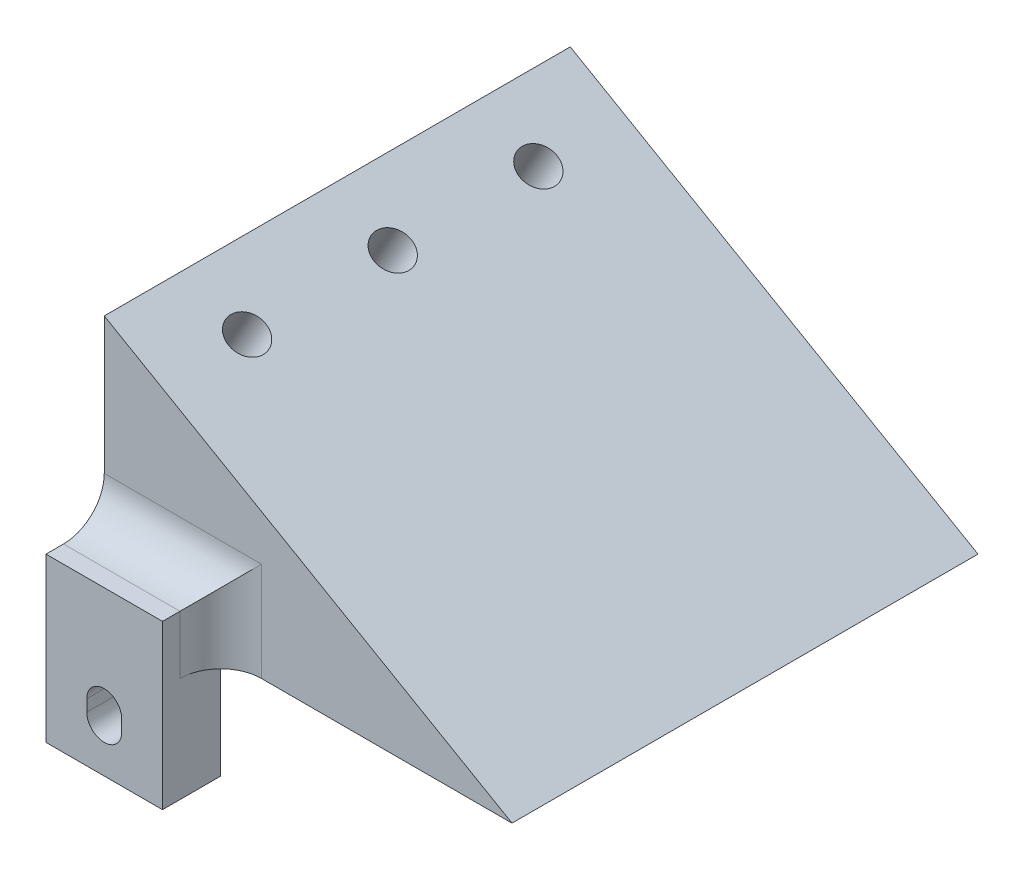
SolidWorks part; units mm, degrees
ref_plane "Front Plane" through (0, 0, 0) normal (0, 0, 1) x (1, 0, 0)
ref_plane "Top Plane" through (0, 0, 0) normal (0, 1, 0) x (1, 0, 0)
ref_plane "Right Plane" through (0, 0, 0) normal (1, 0, 0) x (0, 0, -1)
sketch "Sketch1" plane through (0, 0, 0) normal (0, 0, 1) x (1, 0, 0)
  line L0 (0, 0) -> (0, 40.4145)
  line L1 (0, 40.4145) -> (70, 0)
  line L2 (70, 0) -> (0, 0)
  dimension "D1" = 30
  dimension "D2" = 70
extrude "Boss-Extrude1" add sketch "Sketch1" along normal blind 80
sketch "Sketch2" plane through (0, 0, 80) normal (0, 0, 1) x (1, 0, 0)
  line L0 (0, 40.4145) -> (0, 0) construction
  line L1 (20, 10) -> (0, 10)
  line L2 (20, 10) -> (20, -18)
  line L3 (20, -18) -> (0, -18)
  line L4 (0, 10) -> (0, -18)
  line L5 (20, 10) -> (0, -18) construction
  line L6 (20, -18) -> (0, 10) construction
  line L7 (0, 0) -> (70, 0) construction
  point P0 (10, -4)
  dimension "D1" = 0
  dimension "D2" = 20
  dimension "D3" = 10
  dimension "D4" = 18
extrude "Boss-Extrude2" add sketch "Sketch2" along normal blind 10
fillet "Fillet1" radius 7 2 edges at (20, 5, 80) (10, 10, 80)
sketch "Sketch3" plane through (0, 0, 90) normal (0, 0, 1) x (1, 0, 0)
  line L0 (27, 0) -> (70, 0) construction
  line L1 (10, -10) -> (10, -8) construction
  line L2 (0, -8) -> (20, -8) construction
  line L3 (0, 10) -> (0, -18) construction
  line L4 (20, -18) -> (20, 10) construction
  line L5 (7, -10) -> (7, -8)
  line L6 (13, -10) -> (13, -8)
  arc A1 (7, -10) -> (13, -10) centre (10, -10) ccw
  arc A2 (13, -8) -> (7, -8) centre (10, -8) ccw
  point P11 (10, -9)
  dimension "D2" = 3
  dimension "D1" = 8
  dimension "D3" = 2
ref_plane "Plane1" through (0, 0, 40) normal (0, 0, -1) x (-1, 0, 0)
extrude "Cut-Extrude1" cut sketch "Sketch3" against normal blind 20
mirror "Mirror10" about plane through (0, 0, 40) normal (0, 0, -1) of "Cut-Extrude1", "Boss-Extrude2"
fillet "Fillet2" radius 7 2 edges at (20, 5, 0) (10, 10, 0)
sketch "Sketch4" plane through (17.5, 30.3109, 0) normal (0.5, 0.866, 0) x (0.866, -0.5, 0)
  line L0 (-9.2073, -65) -> (-9.2073, -15) construction
  line L1 (-20.2073, -80) -> (-20.2073, 0) construction
  line L2 (-20.2073, -40) -> (60.6218, -40) construction
  line L3 (60.6218, -80) -> (60.6218, 0) construction
  circle A0 centre (-9.2073, -15) radius 3.2
  circle A1 centre (-9.2073, -40) radius 3.2
  circle A2 centre (-9.2073, -65) radius 3.2
  point P0 (-9.2073, -15)
  point P1 (-9.2073, -40)
  point P2 (-9.2073, -65)
  point P12 (-20.2073, -40)
  dimension "D2" = 6.4
  dimension "D5" = 6.4
  dimension "D6" = 6.4
  dimension "D1" = 50
  dimension "D3" = 11
  dimension "D4" = 11
extrude "Cut-Extrude2" cut sketch "Sketch4" against normal blind 9.5
equation "\"angle\"=30"
equation "\"D1@Sketch1\"=\"angle\""
